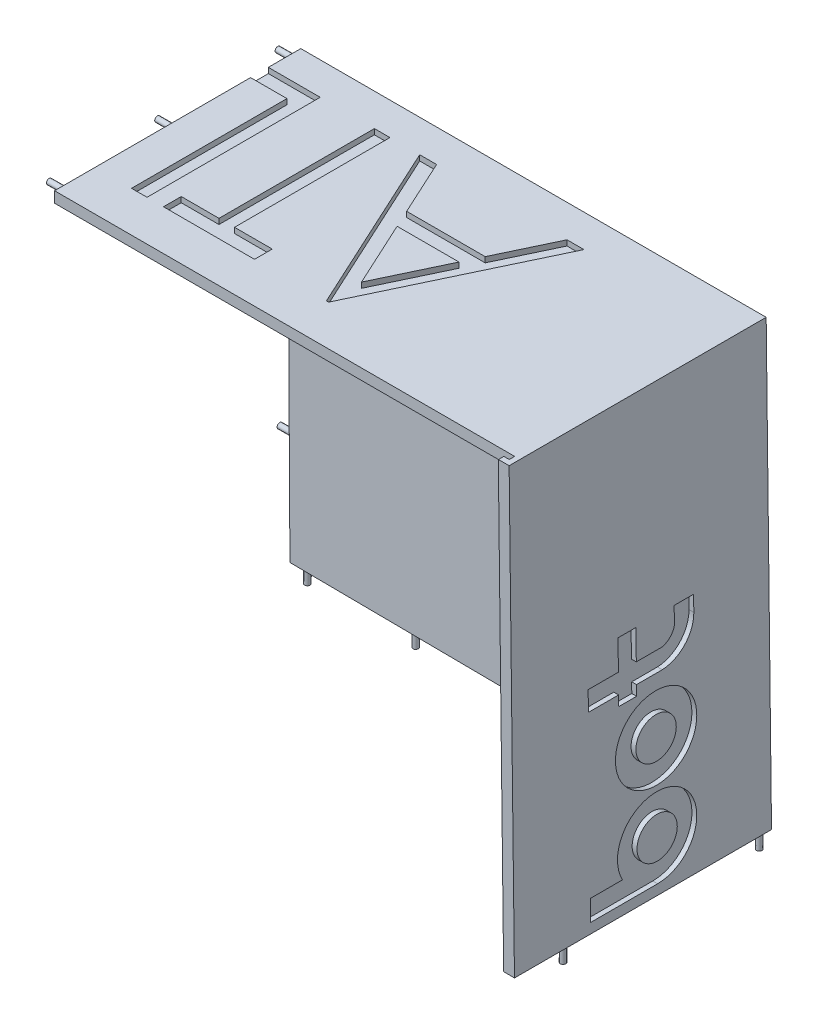
SolidWorks part; units mm, degrees
ref_plane "Alzado" through (0, 0, 0) normal (0, 0, 1) x (1, 0, 0)
ref_plane "Planta" through (0, 0, 0) normal (0, 1, 0) x (1, 0, 0)
ref_plane "Vista lateral" through (0, 0, 0) normal (1, 0, 0) x (0, 0, -1)
sketch "Croquis1" plane through (0, 0, 0) normal (0, 0, 1) x (1, 0, 0)
  line L0 (-86, 80) -> (86, 80) construction
  line L1 (-86, -80) -> (87.9743, -82.988) construction
  line L2 (-86, 80) -> (-86, -80) construction
  line L3 (86, 80) -> (87.9743, -82.988) construction
  line L4 (95.6859, 0) -> (-95.6859, 0) construction
  line L5 (0, -89.6434) -> (0, 89.6434) construction
  line L6 (0, 80) -> (0.9872, -81.494) construction
  line L7 (-86, 0) -> (86.9872, -1.494) construction
  point P1 (0, 80)
  point P3 (-86, 0)
  point P4 (86.9872, -1.494)
  point P5 (0.9872, -81.494)
  dimension "D1" = 174
  dimension "D2" = 172
  dimension "D3" = 160
  dimension "D4" = 163
sketch "Croquis2" plane through (0, 0, 0) normal (0, 0, 1) x (1, 0, 0)
  line L0 (76.1204, 70) -> (2.1204, 70) construction
  line L1 (2.1204, 70) -> (2.1204, -32) construction
  line L2 (2.1204, -32) -> (76.1204, -32) construction
  line L3 (76.1204, -32) -> (76.1204, 70) construction
  line L4 (-86, 80) -> (86, 80) construction
  line L5 (86, 80) -> (87.9743, -82.988) construction
  point P13 (76.1204, 70)
  dimension "D1" = 102
  dimension "D2" = 10
  dimension "D3" = 10
  dimension "D4" = 74
sketch "Croquis3" plane through (0, 0, 0) normal (0, 0, 1) x (1, 0, 0)
  line L0 (-86, 80) -> (86, 80) construction
  line L1 (-86, 80) -> (-86, -80) construction
  line L2 (-81, 70) -> (-19, 70) construction
  line L3 (-19, 70) -> (-19, -25) construction
  line L4 (-19, -25) -> (-81, -25) construction
  line L5 (-81, -25) -> (-81, 70) construction
  line L6 (-19, 58) -> (2.1204, 58) construction
  line L7 (2.1204, 70) -> (2.1204, -32) construction
  line L8 (2.1204, -47) -> (-19, -47) construction
  line L9 (-19, -47) -> (-19, -25) construction
  line L10 (2.1204, -32) -> (2.1204, -47) construction
  point P0 (-81, 70)
  dimension "D1" = 10
  dimension "D2" = 5
  dimension "D3" = 62
  dimension "D4" = 95
  dimension "D5" = 22
  dimension "D6" = 105
sketch "Croquis4" plane through (0, 0, 0) normal (0, 0, 1) x (1, 0, 0)
  line L0 (2.1204, -32) -> (76.1204, -32) construction
  line L1 (22.6942, -40) -> (42.6942, -40) construction
  line L2 (22.6942, -40) -> (22.6942, -41) construction
  line L3 (22.6942, -41) -> (42.6942, -41) construction
  line L4 (72.6942, -41) -> (72.6942, -40) construction
  line L5 (22.6942, -62) -> (42.6942, -62) construction
  line L6 (72.6942, -62) -> (72.6942, -63) construction
  line L7 (72.6942, -63) -> (52.6942, -63) construction
  line L8 (22.6942, -63) -> (22.6942, -62) construction
  line L9 (42.6942, -40) -> (42.6942, -41) construction
  line L11 (52.6942, -63) -> (52.6942, -62) construction
  line L12 (52.6942, -40) -> (72.6942, -40) construction
  line L13 (52.6942, -41) -> (72.6942, -41) construction
  line L14 (42.6942, -62) -> (42.6942, -63) construction
  line L15 (52.6942, -41) -> (52.6942, -40) construction
  line L16 (52.6942, -62) -> (72.6942, -62) construction
  line L17 (42.6942, -63) -> (22.6942, -63) construction
  point P8 (42.6942, -40)
  point P11 (52.6942, -40)
  dimension "D1" = 50
  dimension "D2" = 8
  dimension "D3" = 1
  dimension "D4" = 1
  dimension "D5" = 23
  dimension "D6" = 50
  dimension "D7" = 20
  dimension "D8" = 20
sketch "Croquis6" plane through (0, 0, 0) normal (0, 0, 1) x (1, 0, 0)
  line L0 (-19, -25) -> (-81, -25) construction
  line L1 (-19, -47) -> (-19, -25) construction
  circle A0 centre (-34, -40) radius 12.5 construction
  dimension "D1" = 25
  dimension "D2" = 15
  dimension "D3" = 15
sketch "Croquis7" plane through (0, 0, 0) normal (0, 0, 1) x (1, 0, 0)
  line L0 (2.1204, 70) -> (2.1204, -32) construction
  circle A0 centre (-7.8796, 69.2) radius 7.5 construction
  dimension "D1" = 10
  dimension "D2" = 15
sketch "Croquis8" plane through (0, 0, 0) normal (0, 0, 1) x (1, 0, 0)
  line L0 (-86, -80) -> (87.9743, -82.988) construction
  line L1 (-86, 80) -> (-86, -80) construction
  line L2 (85.9495, -80.953) -> (-84, -78.0341) construction
  line L3 (86, 80) -> (87.9743, -82.988) construction
  line L8 (-84, -78.0341) -> (-84, 78) construction
  line L9 (-84, 78) -> (84.0241, 78) construction
  line L10 (84.0241, 78) -> (85.9495, -80.953) construction
  line L11 (-86, 80) -> (86, 80) construction
  dimension "D1" = 2
  dimension "D2" = 2
  dimension "D3" = 2
  dimension "D4" = 2
sketch "Croquis9" plane through (0, 0, 0) normal (0, 0, 1) x (1, 0, 0)
  line L0 (-71, -25) -> (-71, -78.2573) construction
  line L1 (-86, 80) -> (-86, -80) construction
  line L4 (85.9495, -80.953) -> (-84, -78.0341) construction
  line L5 (-19, -25) -> (-81, -25) construction
  circle A0 centre (-71, -35) radius 0.5 construction
  circle A1 centre (-71, -47) radius 0.5 construction
  circle A2 centre (-71, -55) radius 0.5 construction
  circle A3 centre (-71, -67) radius 0.5 construction
  point P4 (-71, -35)
  point P9 (-71, -47)
  point P10 (-71, -55)
  point P11 (-71, -67)
  dimension "D6" = 1
  dimension "D7" = 1
  dimension "D8" = 1
  dimension "D9" = 1
  dimension "D1" = 15
  dimension "D2" = 10
  dimension "D3" = 12
  dimension "D4" = 8
  dimension "D5" = 12
sketch "Croquis10" plane through (0, 0, 0) normal (0, 0, 1) x (1, 0, 0)
  line L0 (-71, -25) -> (-71, -78.2573) construction
  line L1 (-86, -80) -> (87.9743, -82.988) construction
  line L2 (-53, -43.2562) -> (-71, -43.2562) construction
  line L3 (-53, -70.2562) -> (-71, -70.2562) construction
  line L4 (-71, -70.2562) -> (-71, -69.2562) construction
  line L5 (-71, -69.2562) -> (-53, -69.2562) construction
  line L6 (-53, -69.2562) -> (-53, -70.2562) construction
  line L7 (-71, -43.2562) -> (-71, -44.2562) construction
  line L8 (-71, -44.2562) -> (-53, -44.2562) construction
  line L9 (-53, -44.2562) -> (-53, -43.2562) construction
  line L10 (-86, 80) -> (-86, -80) construction
  point P0 (-71, -70.2562)
  point P1 (-71, -43.2562)
  dimension "D1" = 27
  dimension "D2" = 10
  dimension "D3" = 1
  dimension "D4" = 1
  dimension "D5" = 18
  dimension "D6" = 18
  dimension "D7" = 15
  dimension "D8" = 15
sketch "Croquis11" plane through (0, 0, 0) normal (0, 0, 1) x (1, 0, 0)
  line L0 (-86, -80) -> (87.9743, -82.988) construction
  line L1 (84.0241, 78) -> (85.9495, -80.953) construction
  line L2 (-86, 80) -> (-86, -80) construction
  circle A0 centre (-4.2697, -63.4011) radius 14 construction
  circle A1 centre (-34, -65.8909) radius 10 construction
  dimension "D1" = 18
  dimension "D2" = 28
  dimension "D4" = 20
  dimension "D3" = 90
  dimension "D5" = 15
  dimension "D6" = 52
sketch "Croquis12" plane through (0, 0, 0) normal (0, 0, 1) x (1, 0, 0)
  line L0 (-86, 80) -> (86, 80) construction
  line L1 (-86, 80) -> (-86, -80) construction
  line L3 (86, 80) -> (87.9743, -82.988) construction
  line L4 (-86, -80) -> (87.9743, -82.988) construction
  circle A0 centre (-80, -73.102) radius 2 construction
  circle A1 centre (-80, 74) radius 2 construction
  circle A2 centre (79.0722, 74) radius 2 construction
  circle A3 centre (80.8997, -76.8656) radius 2 construction
  point P0 (-80, 74)
  point P1 (79.0722, 74)
  point P2 (80.8997, -76.8656)
  point P3 (-80, -73.102)
  dimension "D1" = 6
  dimension "D2" = 6
  dimension "D3" = 6
  dimension "D4" = 7
  dimension "D5" = 7
  dimension "D6" = 6
  dimension "D7" = 7
  dimension "D8" = 6
sketch "Croquis13" plane through (0, 0, 0) normal (0, 0, 1) x (1, 0, 0)
  line L0 (76.1204, 70) -> (2.1204, 70) construction
  line L1 (76.1204, -32) -> (76.1204, 70) construction
  line L2 (2.1204, -32) -> (76.1204, -32) construction
  circle A0 centre (72.1204, 63) radius 1.5 construction
  circle A1 centre (72.1204, -26) radius 1.5 construction
  point P0 (72.1204, 63)
  point P7 (72.1204, -26)
  dimension "D3" = 3
  dimension "D6" = 3
  dimension "D1" = 7
  dimension "D2" = 4
  dimension "D4" = 89
  dimension "D5" = 6
sketch "Croquis14" plane through (0, 0, 0) normal (0, 0, 1) x (1, 0, 0)
  line L1 (-19, 70) -> (-19, -25) construction
  line L2 (-19, -25) -> (-81, -25) construction
  circle A0 centre (-49, 45) radius 1.5 construction
  circle A1 centre (-49, -10) radius 1.5 construction
  point P0 (-49, 45)
  point P1 (-49, -10)
  dimension "D3" = 3
  dimension "D4" = 3
  dimension "D1" = 30
  dimension "D2" = 30
  dimension "D5" = 55
  dimension "D6" = 15
sketch "Croquis15" plane through (0, 0, 0) normal (0, 0, 1) x (1, 0, 0)
  line L0 (0, 80) -> (86, 80)
  line L1 (86, 80) -> (86.9872, -1.494)
  line L2 (86.9872, -1.494) -> (0.4936, -0.747)
  line L3 (-86, 0) -> (86.9872, -1.494) construction
  line L4 (0.4936, -0.747) -> (0, 80)
extrude "Saliente-Extruir1" add sketch "Croquis15" along normal blind 2.5
sketch "Croquis16" plane through (0, 0, 2.5) normal (0, 0, 1) x (1, 0, 0)
  line L0 (0, 80) -> (0.012, 78)
  line L1 (-84, 78) -> (84.0241, 78) construction
  line L2 (0.012, 78) -> (84.0241, 78)
  line L3 (84.0241, 78) -> (84.9868, -1.4765)
  line L5 (84.0241, 78) -> (85.9495, -80.953) construction
  line L6 (86.9872, -1.494) -> (86, 80)
  line L7 (86, 80) -> (0, 80)
  line L8 (84.9868, -1.4765) -> (86.9872, -1.494)
extrude "Saliente-Extruir2" add sketch "Croquis16" along normal blind 45
sketch "Croquis17" plane through (0, 0, 2.5) normal (0, 0, 1) x (1, 0, 0)
  circle A0 centre (79.0722, 74) radius 2
  circle A1 centre (72.1204, 63) radius 1.5
extrude "Cortar-Extruir1" cut sketch "Croquis17" against normal blind 45
sketch "Croquis18" plane through (-0.0064, -0.7427, 0) normal (-0.0086, -1, 0) x (1, -0.0086, 0)
  line L0 (0.5, 1.25) -> (86.9968, 1.25) construction
  line L2 (0.5, 2.5) -> (0.5, 0) construction
  line L5 (86.9968, 2.5) -> (86.9968, 0) construction
  circle A0 centre (2.5, 1.25) radius 0.5
  circle A1 centre (85.9968, 1.25) radius 0.5
  circle A2 centre (22.5, 1.25) radius 0.5
  circle A3 centre (65.9968, 1.25) radius 0.5
  circle A4 centre (43.4968, 1.25) radius 0.5
  point P6 (2.5, 1.25)
  point P9 (22.5, 1.25)
  point P10 (43.4968, 1.25)
  point P11 (85.9968, 1.25)
  point P12 (65.9968, 1.25)
  dimension "D1" = 2
  dimension "D3" = 20
  dimension "D5" = 22.5
  dimension "D2" = 1
  dimension "D4" = 20
extrude "Saliente-Extruir3" add sketch "Croquis18" along normal blind 3
sketch "Croquis19" plane through (0, 80, 0) normal (0, 1, 0) x (1, 0, 0)
  line L0 (0, -47.5) -> (0, -2.5) construction
  line L1 (84, -47.5) -> (84, -45.5)
  line L2 (0, -45.5) -> (84, -45.5)
  line L3 (0, -45.5) -> (0, -47.5)
  line L4 (0, -47.5) -> (84, -47.5)
  dimension "D1" = 2
extrude "Cortar-Extruir2" cut sketch "Croquis19" against normal blind 10
sketch "Croquis24" plane through (0, 0, 47.5) normal (0, 0, 1) x (1, 0, 0)
  line L0 (84, 78) -> (84.0241, 78)
  line L1 (84.0241, 78) -> (84.0241, 80)
  line L2 (86, 80) -> (84, 80) construction
  line L3 (84.0241, 80) -> (84, 80)
  line L4 (84, 80) -> (84, 78)
extrude "Cortar-Extruir11" cut sketch "Croquis24" against normal up to surface (2 mm away) up to face at (42.003, 79, 45.5)
sketch "Croquis30" plane through (0, 80, 0) normal (0, 1, 0) x (1, 0, 0)
  line L1 (84.0241, -45.5) -> (85.0241, -45.5)
  line L2 (84.0241, -45.5) -> (84.0241, -46.5)
  line L3 (84.0241, -46.5) -> (85.0241, -46.5)
  line L4 (85.0241, -45.5) -> (85.0241, -46.5)
  dimension "D1" = 1
  dimension "D2" = 1
extrude "Cortar-Extruir12" cut sketch "Croquis30" against normal blind 101
sketch "Croquis32" plane through (84.9565, 1.0291, 0) normal (-0.9999, -0.0121, 0) x (0, 0, 1)
  line L1 (45.5, 76.9765) -> (46.5, 76.9765)
  line L2 (45.5, 76.9765) -> (45.5, -2.5058)
  line L3 (45.5, -2.5058) -> (46.5, -2.5058)
  line L4 (46.5, 76.9765) -> (46.5, -2.5058)
extrude "Cortar-Extruir13" cut sketch "Croquis32" against normal blind 1
sketch "Croquis33" plane through (-0.0064, -0.7314, 0) normal (-0.0088, -1, 0) x (1, -0.0088, 0)
  line L1 (84.9965, 46.5) -> (85.9965, 46.5)
  line L2 (84.9965, 46.5) -> (84.9965, 45.5)
  line L3 (84.9965, 45.5) -> (85.9965, 45.5)
  line L4 (85.9965, 46.5) -> (85.9965, 45.5)
  dimension "D1" = 1
extrude "Cortar-Extruir14" cut sketch "Croquis33" against normal blind 1
sketch "Croquis35" plane through (-0.0064, -0.7314, 0) normal (-0.0088, -1, 0) x (1, -0.0088, 0)
  line L0 (84.9965, 2.5) -> (86.9969, 2.5) construction
  circle A0 centre (85.9967, 37.5) radius 0.5
  point P0 (85.9967, 37.5)
  point P1 (85.9967, 17.5)
  dimension "D1" = 15
  dimension "D2" = 20
extrude "Saliente-Extruir4" add sketch "Croquis35" along normal blind 3
sketch "Croquis37" plane through (-0.0064, -0.7314, 0) normal (-0.0088, -1, 0) x (1, -0.0088, 0)
  line L1 (84.9965, 2.5) -> (86.9969, 2.5) construction
  circle A2 centre (85.9969, 9.5) radius 0.5
  dimension "D3" = 7
extrude "Cortar-Extruir15" cut sketch "Croquis37" against normal blind 4
sketch "Croquis38" plane through (-0.0064, -0.7427, 0) normal (-0.0086, -1, 0) x (1, -0.0086, 0)
  line L2 (0.5, 2.5) -> (0.5, 0) construction
  circle A0 centre (12.5, 1.25) radius 0.5
  circle A1 centre (32.5, 1.25) radius 0.5
  circle A2 centre (55, 1.25) radius 0.5
  circle A3 centre (77, 1.25) radius 0.5
  dimension "D1" = 12
  dimension "D2" = 20
  dimension "D3" = 22.5
  dimension "D4" = 22
extrude "Cortar-Extruir16" cut sketch "Croquis38" against normal blind 4
sketch "Croquis39" plane through (0, 80, 0) normal (0, 1, 0) x (1, 0, 0)
  line L0 (59.9709, -6) -> (0, -6) construction
  line L2 (0, -45.5) -> (0, -2.5) construction
  line L3 (-86, 0) -> (86, 0) construction
  text T0 "ATL" font "Century Gothic" height 32
  dimension "D1" = 6
extrude "Cortar-Extruir17" cut sketch "Croquis39" against normal blind 1
sketch "Croquis40" plane through (86.9563, 1.0533, 0) normal (0.9999, 0.0121, 0) x (0, 0, -1)
  line L0 (-21.0265, -0.7136) -> (-33.4119, -0.7136)
  line L1 (-33.4119, -0.7136) -> (-33.4119, 3.1104)
  line L2 (-33.4119, 3.1104) -> (-27.4613, 3.1104)
  line L3 (-24.518, 36.3192) -> (-24.518, 41.7918)
  line L4 (-27.8251, 30.8467) -> (-24.518, 30.8467)
  line L5 (-27.8251, 30.8467) -> (-27.8251, 32.706)
  line L6 (-27.8251, 41.7918) -> (-24.518, 41.7918)
  line L7 (-24.518, 30.8467) -> (-24.518, 32.706)
  line L8 (-33.4119, 32.706) -> (-27.8251, 32.706)
  line L9 (-33.4119, 32.706) -> (-33.4119, 36.3192)
  line L10 (-33.4119, 36.3192) -> (-27.8251, 36.3192)
  line L11 (-24.518, 36.3192) -> (-19.754, 36.3192)
  line L12 (-17.4515, 41.7918) -> (-13.8592, 41.7918)
  line L13 (-24.518, 32.706) -> (-19.754, 32.706)
  line L14 (-27.8251, 36.3192) -> (-27.8251, 41.7918)
  line L15 (-13.8592, 41.7918) -> (-13.8592, 38.9006)
  line L16 (-17.4515, 38.5739) -> (-17.4515, 41.7918)
  circle A0 centre (-21.0265, 6.6127) radius 3.7227
  arc A1 (-21.0265, -0.7136) -> (-27.4613, 3.1104) centre (-21.0265, 6.6127) ccw
  circle A2 centre (-21.0265, 22.4727) radius 3.7283
  circle A3 centre (-21.0265, 22.4727) radius 7.5159
  arc A4 (-19.754, 36.3192) -> (-17.4515, 38.5739) centre (-20.4308, 39.3134) ccw
  arc A5 (-19.754, 32.706) -> (-13.8592, 38.9006) centre (-20.0613, 38.9006) ccw
  point P21 (-17.4515, 38.5739)
extrude "Cortar-Extruir19" cut sketch "Croquis40" against normal blind 0.9
sketch "Croquis41" plane through (0.489, 0.003, 0) normal (-1, -0.0061, 0) x (0, 0, 1)
  line L0 (1.25, 79.9985) -> (1.25, 9.4985) construction
  line L1 (2.5, 79.9985) -> (0, 79.9985) construction
  line L2 (2.5, -0.75) -> (0, -0.75) construction
  line L3 (1.25, 8.4985) -> (1.25, -0.75) construction
  circle A0 centre (1.25, 78.9985) radius 0.5
  circle A1 centre (1.25, 58.9985) radius 0.5
  circle A2 centre (1.25, 38.9985) radius 0.5
  circle A5 centre (1.25, 18.9985) radius 0.5
  dimension "D1" = 1
  dimension "D2" = 20
  dimension "D3" = 20
  dimension "D4" = 20
extrude "Saliente-Extruir5" add sketch "Croquis41" along normal blind 3
sketch "Croquis42" plane through (0.4816, 0.0029, 0) normal (-1, -0.006, 0) x (0, 0, 1)
  line L0 (45.5, 78.9985) -> (34, 78.9985) construction
  line L1 (45.5, 77.9985) -> (45.5, 79.9986) construction
  line L2 (33, 78.9985) -> (14, 78.9985) construction
  line L3 (13, 78.9985) -> (2.5271, 78.9985) construction
  circle A1 centre (43.5, 78.9985) radius 0.5
  circle A3 centre (23.5, 78.9985) radius 0.5
  dimension "D1" = 2
extrude "Saliente-Extruir6" add sketch "Croquis42" along normal blind 3
sketch "Croquis45" plane through (0.4816, 0.0029, 0) normal (-1, -0.006, 0) x (0, 0, 1)
  line L0 (45.5, 77.9985) -> (45.5, 79.9986) construction
  circle A0 centre (33.5, 78.9985) radius 0.5
  circle A1 centre (13.5, 78.9985) radius 0.5
  dimension "D1" = 12
  dimension "D2" = 20
extrude "Cortar-Extruir22" cut sketch "Croquis45" against normal blind 4
sketch "Croquis46" plane through (0.489, 0.003, 0) normal (-1, -0.0061, 0) x (0, 0, 1)
  line L0 (1.25, 79.9985) -> (1.25, 0.9406) construction
  line L1 (2.5, 79.9985) -> (0, 79.9985) construction
  circle A0 centre (1.25, 68.9985) radius 0.5
  circle A1 centre (1.25, 48.9985) radius 0.5
  circle A2 centre (1.25, 28.9985) radius 0.5
  circle A3 centre (1.25, 8.9985) radius 0.5
  dimension "D1" = 11
  dimension "D2" = 20
  dimension "D3" = 20
  dimension "D4" = 20
extrude "Cortar-Extruir23" cut sketch "Croquis46" against normal blind 4
